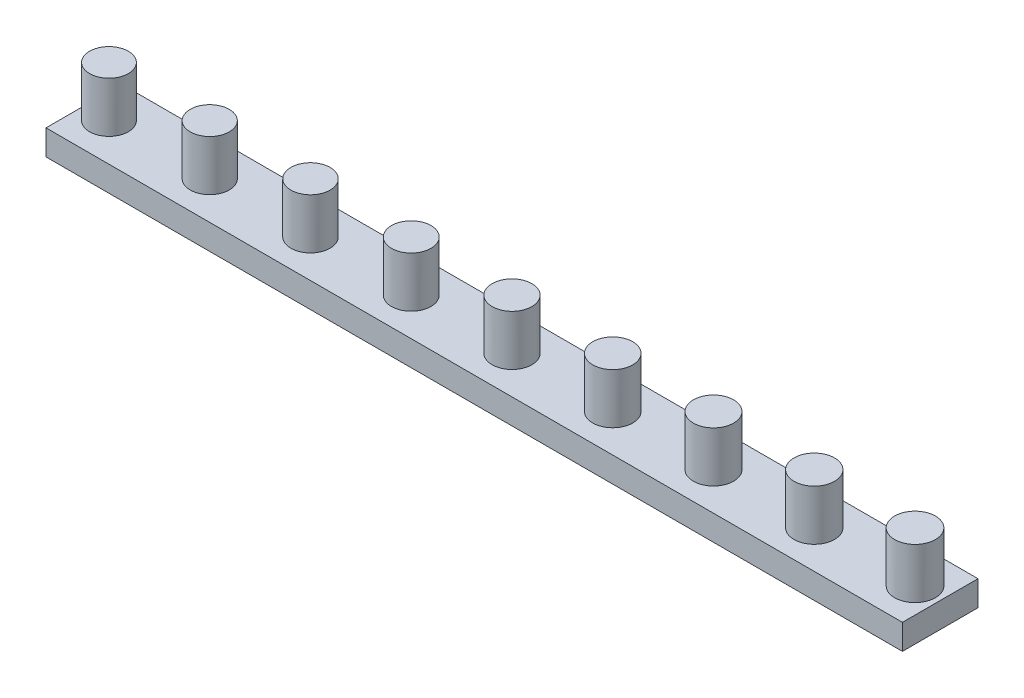
SolidWorks part; units mm, degrees
ref_plane "정면" through (0, 0, 0) normal (0, 0, 1) x (1, 0, 0)
ref_plane "윗면" through (0, 0, 0) normal (0, 1, 0) x (1, 0, 0)
ref_plane "우측면" through (0, 0, 0) normal (1, 0, 0) x (0, 0, -1)
sketch "스케치3" plane through (0, 0, 0) normal (0, 1, 0) x (1, 0, 0)
  line L1 (-85, -7.5) -> (85, -7.5)
  line L2 (-85, -7.5) -> (-85, 7.5)
  line L3 (-85, 7.5) -> (85, 7.5)
  line L4 (85, -7.5) -> (85, 7.5)
  line L5 (-85, -7.5) -> (85, 7.5) construction
  line L6 (-85, 7.5) -> (85, -7.5) construction
  point P0 (0, 0)
  dimension "D1" = 170
  dimension "D2" = 15
extrude "보스-돌출3" add sketch "스케치3" along normal blind 5
sketch "스케치4" plane through (0, 5, 0) normal (0, 1, 0) x (1, 0, 0)
  line L0 (-85, 7.5) -> (-85, -7.5) construction
  circle A0 centre (-80, 0) radius 3.85
  circle A1 centre (-60, 0) radius 3.875
  circle A2 centre (-40, 0) radius 3.9
  circle A3 centre (-20, 0) radius 3.925
  circle A4 centre (0, 0) radius 3.95
  circle A5 centre (20, 0) radius 3.975
  circle A6 centre (40, 0) radius 4
  circle A7 centre (60, 0) radius 4.025
  circle A8 centre (80, 0) radius 4.05
  point P20 (0, 0)
  dimension "D1" = 7.7
  dimension "D4" = 7.75
  dimension "D6" = 7.8
  dimension "D7" = 7.85
  dimension "D10" = 7.9
  dimension "D12" = 7.95
  dimension "D14" = 8
  dimension "D17" = 8.05
  dimension "D18" = 8.1
  dimension "D2" = 5
  dimension "D3" = 20
  dimension "D5" = 20
  dimension "D8" = 20
  dimension "D9" = 20
  dimension "D11" = 20
  dimension "D13" = 20
  dimension "D15" = 20
  dimension "D16" = 20
extrude "보스-돌출4" add sketch "스케치4" along normal blind 10
